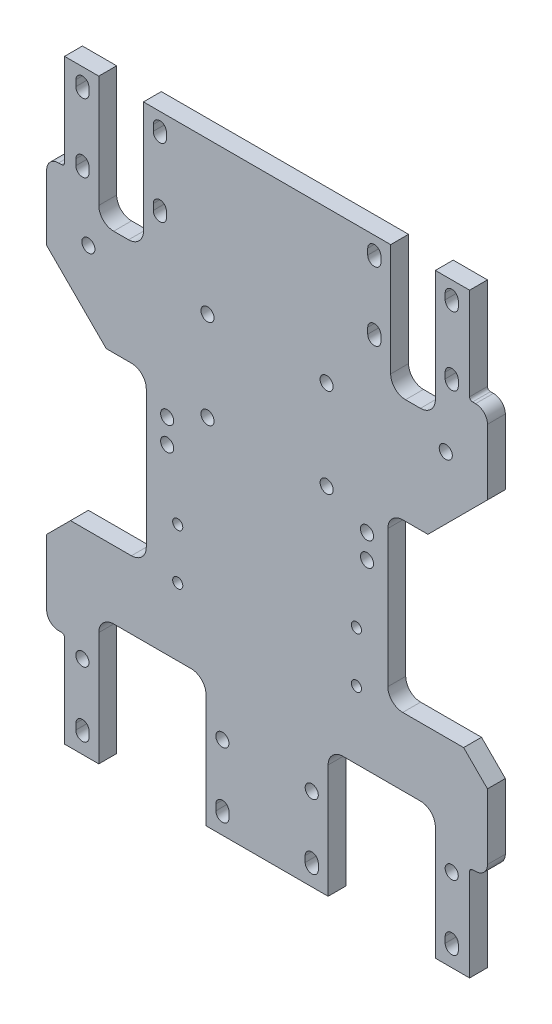
SolidWorks part; units mm, degrees
ref_plane "Front Plane" through (0, 0, 0) normal (0, 0, 1) x (1, 0, 0)
ref_plane "Top Plane" through (0, 0, 0) normal (0, 1, 0) x (1, 0, 0)
ref_plane "Right Plane" through (0, 0, 0) normal (1, 0, 0) x (0, 0, -1)
ref_plane "Plane1" through (0, 0, 3) normal (0, 0, 1) x (1, 0, 0)
sketch "Sketch1" plane through (0, 0, 3) normal (0, 0, 1) x (1, 0, 0)
  line L0 (38.2, 95.1) -> (38.2, 93.1)
  line L1 (33.8, 93.1) -> (33.8, 95.1)
  line L2 (64.2, 72.1) -> (64.2, 70.1)
  line L3 (59.8, 70.1) -> (59.8, 72.1)
  line L4 (-38.2, 70.1) -> (-38.2, 72.1)
  line L5 (-33.8, 72.1) -> (-33.8, 70.1)
  line L6 (-64.2, 93.1) -> (-64.2, 95.1)
  line L7 (-59.8, 95.1) -> (-59.8, 93.1)
  line L8 (12.8, -94) -> (12.8, -92)
  line L9 (17.2, -92) -> (17.2, -94)
  line L10 (-12.8, -92) -> (-12.8, -94)
  line L11 (-17.2, -94) -> (-17.2, -92)
  line L12 (-59.8, -92) -> (-59.8, -94)
  line L13 (-64.2, -94) -> (-64.2, -92)
  line L14 (59.8, -94) -> (59.8, -92)
  line L15 (64.2, -92) -> (64.2, -94)
  line L16 (-64.2, 70.1) -> (-64.2, 72.1)
  line L17 (-59.8, 72.1) -> (-59.8, 70.1)
  line L18 (-38.2, 93.1) -> (-38.2, 95.1)
  line L19 (-33.8, 95.1) -> (-33.8, 93.1)
  line L20 (64.2, 95.1) -> (64.2, 93.1)
  line L21 (59.8, 93.1) -> (59.8, 95.1)
  line L22 (38.2, 72.1) -> (38.2, 70.1)
  line L23 (33.8, 70.1) -> (33.8, 72.1)
  line L24 (40.5551, -29) -> (40.5551, 17)
  line L25 (45.5551, 22) -> (54, 22)
  line L26 (54, 22) -> (74, 42)
  line L27 (74, 42) -> (74, 64)
  line L28 (70, 68) -> (69, 68)
  line L29 (68, 69) -> (68, 100)
  line L30 (68, 100) -> (56.5, 100)
  line L31 (56.5, 100) -> (56.5, 62.4)
  line L32 (51.5, 57.4) -> (46.5, 57.4)
  line L33 (41.5, 62.4) -> (41.5, 100)
  line L34 (41.5, 100) -> (-41.5, 100)
  line L35 (-41.5, 100) -> (-41.5, 62.4)
  line L36 (-46.5, 57.4) -> (-51.5, 57.4)
  line L37 (-56.5, 62.4) -> (-56.5, 100)
  line L38 (-56.5, 100) -> (-68, 100)
  line L39 (-68, 100) -> (-68, 69)
  line L40 (-69, 68) -> (-70, 68)
  line L41 (-74, 64) -> (-74, 42)
  line L42 (-74, 42) -> (-54, 22)
  line L43 (-54, 22) -> (-45.5551, 22)
  line L44 (-40.5551, 17) -> (-40.5551, -29)
  line L45 (-45.5551, -34) -> (-66, -34)
  line L46 (-66, -34) -> (-74, -42)
  line L47 (-74, -42) -> (-74, -64)
  line L48 (-70, -68) -> (-69, -68)
  line L49 (-68, -69) -> (-68, -100)
  line L50 (-68, -100) -> (-56.5, -100)
  line L51 (-56.5, -100) -> (-56.5, -61.8)
  line L52 (-51.5, -56.8) -> (-25.5, -56.8)
  line L53 (-20.5, -61.8) -> (-20.5, -100)
  line L54 (-20.5, -100) -> (20.5, -100)
  line L55 (20.5, -100) -> (20.5, -61.8)
  line L56 (25.5, -56.8) -> (51.5, -56.8)
  line L57 (56.5, -61.8) -> (56.5, -100)
  line L58 (56.5, -100) -> (68, -100)
  line L59 (68, -100) -> (68, -69)
  line L60 (69, -68) -> (70, -68)
  line L61 (74, -64) -> (74, -42)
  line L62 (74, -42) -> (66, -34)
  line L63 (66, -34) -> (45.5551, -34)
  circle A0 centre (-20, 19) radius 2.2
  circle A1 centre (60, 49) radius 2.2
  circle A2 centre (20, 49) radius 2.2
  circle A3 centre (33.5551, 4.3) radius 2.2
  circle A4 centre (30, -17.1) radius 1.7
  circle A5 centre (-33.5551, 12.3) radius 2.2
  circle A6 centre (-30, -34.1) radius 1.7
  arc A7 (33.8, 95.1) -> (38.2, 95.1) centre (36, 95.1) cw
  arc A8 (38.2, 93.1) -> (33.8, 93.1) centre (36, 93.1) cw
  arc A9 (59.8, 72.1) -> (64.2, 72.1) centre (62, 72.1) cw
  arc A10 (64.2, 70.1) -> (59.8, 70.1) centre (62, 70.1) cw
  arc A11 (-38.2, 72.1) -> (-33.8, 72.1) centre (-36, 72.1) cw
  arc A12 (-33.8, 70.1) -> (-38.2, 70.1) centre (-36, 70.1) cw
  arc A13 (-64.2, 95.1) -> (-59.8, 95.1) centre (-62, 95.1) cw
  arc A14 (-59.8, 93.1) -> (-64.2, 93.1) centre (-62, 93.1) cw
  arc A15 (17.2, -94) -> (12.8, -94) centre (15, -94) cw
  arc A16 (12.8, -92) -> (17.2, -92) centre (15, -92) cw
  circle A17 centre (62, -72.2) radius 2.2
  arc A18 (-12.8, -94) -> (-17.2, -94) centre (-15, -94) cw
  arc A19 (-17.2, -92) -> (-12.8, -92) centre (-15, -92) cw
  circle A20 centre (-62, -72.2) radius 2.2
  circle A21 centre (-15, -72.2) radius 2.2
  arc A22 (-59.8, -94) -> (-64.2, -94) centre (-62, -94) cw
  arc A23 (-64.2, -92) -> (-59.8, -92) centre (-62, -92) cw
  circle A24 centre (15, -72.2) radius 2.2
  arc A25 (64.2, -94) -> (59.8, -94) centre (62, -94) cw
  arc A26 (59.8, -92) -> (64.2, -92) centre (62, -92) cw
  arc A27 (-64.2, 72.1) -> (-59.8, 72.1) centre (-62, 72.1) cw
  arc A28 (-59.8, 70.1) -> (-64.2, 70.1) centre (-62, 70.1) cw
  arc A29 (-38.2, 95.1) -> (-33.8, 95.1) centre (-36, 95.1) cw
  arc A30 (-33.8, 93.1) -> (-38.2, 93.1) centre (-36, 93.1) cw
  arc A31 (59.8, 95.1) -> (64.2, 95.1) centre (62, 95.1) cw
  arc A32 (64.2, 93.1) -> (59.8, 93.1) centre (62, 93.1) cw
  arc A33 (33.8, 72.1) -> (38.2, 72.1) centre (36, 72.1) cw
  arc A34 (38.2, 70.1) -> (33.8, 70.1) centre (36, 70.1) cw
  circle A35 centre (-30, -17.1) radius 1.7
  circle A36 centre (-33.5551, 4.3) radius 2.2
  circle A37 centre (30, -34.1) radius 1.7
  arc A38 (45.5551, -34) -> (40.5551, -29) centre (45.5551, -29) cw
  arc A39 (40.5551, 17) -> (45.5551, 22) centre (45.5551, 17) cw
  arc A40 (74, 64) -> (70, 68) centre (70, 64) ccw
  arc A41 (69, 68) -> (68, 69) centre (69, 69) cw
  arc A42 (56.5, 62.4) -> (51.5, 57.4) centre (51.5, 62.4) cw
  arc A43 (46.5, 57.4) -> (41.5, 62.4) centre (46.5, 62.4) cw
  arc A44 (-41.5, 62.4) -> (-46.5, 57.4) centre (-46.5, 62.4) cw
  arc A45 (-51.5, 57.4) -> (-56.5, 62.4) centre (-51.5, 62.4) cw
  arc A46 (-68, 69) -> (-69, 68) centre (-69, 69) cw
  arc A47 (-70, 68) -> (-74, 64) centre (-70, 64) ccw
  arc A48 (-45.5551, 22) -> (-40.5551, 17) centre (-45.5551, 17) cw
  arc A49 (-40.5551, -29) -> (-45.5551, -34) centre (-45.5551, -29) cw
  arc A50 (-74, -64) -> (-70, -68) centre (-70, -64) ccw
  arc A51 (-69, -68) -> (-68, -69) centre (-69, -69) cw
  arc A52 (-56.5, -61.8) -> (-51.5, -56.8) centre (-51.5, -61.8) cw
  arc A53 (-25.5, -56.8) -> (-20.5, -61.8) centre (-25.5, -61.8) cw
  arc A54 (20.5, -61.8) -> (25.5, -56.8) centre (25.5, -61.8) cw
  arc A55 (51.5, -56.8) -> (56.5, -61.8) centre (51.5, -61.8) cw
  arc A56 (68, -69) -> (69, -68) centre (69, -69) cw
  arc A57 (70, -68) -> (74, -64) centre (70, -64) ccw
  circle A58 centre (33.5551, 12.3) radius 2.2
  circle A59 centre (20, 19) radius 2.2
  circle A60 centre (-20, 49) radius 2.2
  circle A61 centre (-60, 49) radius 2.2
extrude "Boss-Extrude1" add sketch "Sketch1" against normal blind 6
